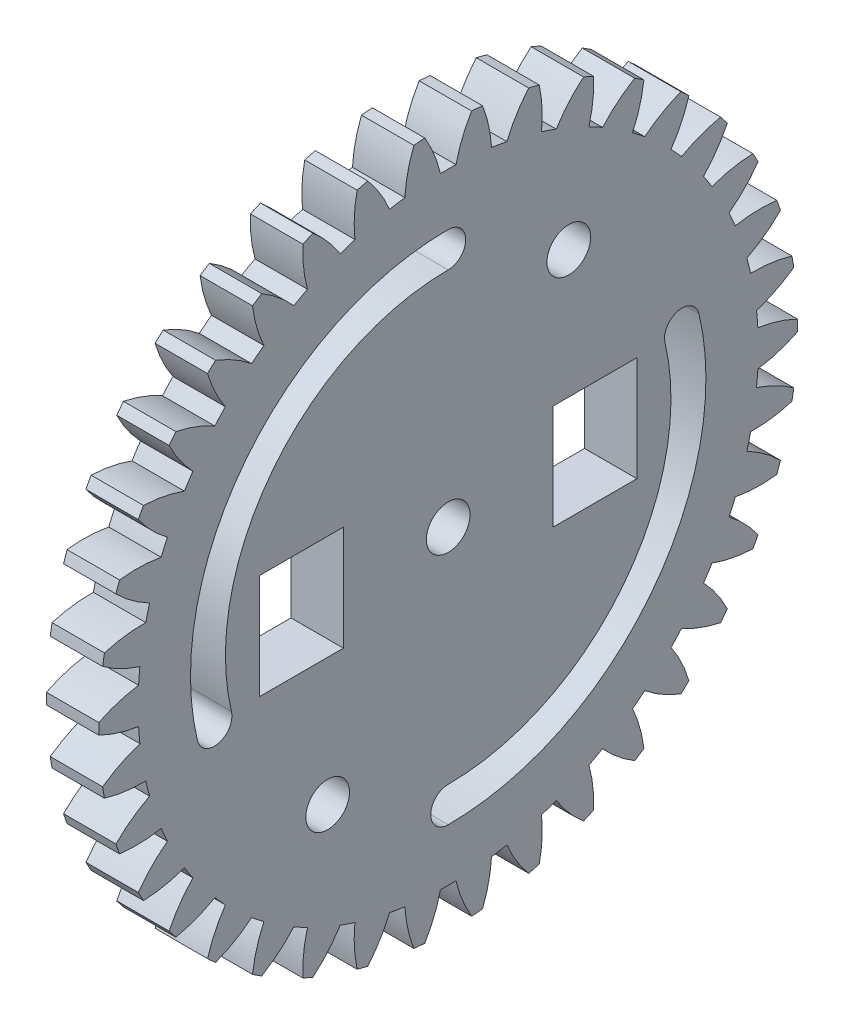
SolidWorks part; units mm, degrees
ref_plane "Plane1" through (0, 0, 0) normal (0, 0, 1) x (1, 0, 0)
ref_plane "Plane2" through (0, 0, 0) normal (0, 1, 0) x (1, 0, 0)
ref_plane "Plane3" through (0, 0, 0) normal (1, 0, 0) x (0, 0, -1)
sketch "HoldingSke" plane through (0, 0, 0) normal (0, 1, 0) x (1, 0, 0)
  line L0 (0, 0) -> (0.394, -0.3078)
  line L1 (-15, 0) -> (100, 0) construction
  line L2 (0, 0) -> (-2.1039, 2.3779)
  line L3 (0, 0) -> (-11.863, 4.5341)
  line L4 (0, 0) -> (6.8053, 5.3169)
  line L5 (0, 0) -> (-46.8476, -17.4728)
  line L6 (0, 0) -> (-4.9738, -3.3558)
  line L7 (-2.1039, 2.3779) -> (8.6586, 51.2059)
  line L8 (-76.2, 54.61) -> (-75.5, 54.61)
  line L9 (-71.009, 38.7566) -> (-53.1078, 45.2721)
  line L10 (-76.2, 71.12) -> (104.1128, 71.12)
  line L11 (0, 0) -> (-6, 0)
  line L12 (-76.2, 101.6) -> (-76.133, 101.6)
  line L13 (24.9733, 27.94) -> (52.9518, 28.4284)
  line L14 (24.9733, 27.94) -> (24.9743, 27.94)
  line L15 (24.9733, 27.94) -> (100.4006, 29.5858)
  line L16 (-63.627, -2) -> (-12.827, -2)
  circle A0 centre (0, 0) radius 2
  circle A1 centre (0, 0) radius 35.499
  circle A2 centre (0, 0) radius 37.5
  circle A3 centre (0, 0) radius 2
  dimension "MHD" = 70.998
  dimension "Hub_dia" = 75
  dimension "Bore" = 4
  dimension "MBD" = 4
  dimension "Num_teeth" = 38
  dimension "Pitch" = 0.5
  dimension "Overall_len" = 50
  dimension "Show_teeth" = 38
  dimension "Thickness" = 6
  dimension "OAL" = 50.0001
  dimension "T_dim" = 0.7
  dimension "Ap" = 20
  dimension "H" = 19.05
  dimension "Pitch_radius" = 180.3128
  dimension "Width" = 6
  dimension "Backlash" = 0.067
  dimension "Addendum_fac" = 1
  dimension "Dedendum_fac" = 1.25
  dimension "Clearance_fac" = 0.25
  dimension "Dedendum_add" = 0.001
  dimension "Module" = 2
sketch "BasProSke" plane through (0, 0, 0) normal (0, 1, 0) x (1, 0, 0)
  line L0 (-10, 0) -> (60, 0) construction
  line L1 (0, 0) -> (0, 40)
  line L2 (0, 0) -> (6, 0)
  line L3 (6, 0) -> (6, 40)
  line L4 (6, 40) -> (0, 40)
  dimension "Thickness" = 6
  dimension "Diameter" = 80
revolve "Base-Revolve" add sketch "BasProSke" angle 360 about L0
sketch "TooCutSke" plane through (0, 0, 0) normal (1, 0, 0) x (0, 0, -1)
  line L1 (0, 0) -> (0, 107) construction
  line L2 (0, 0) -> (-1.6876, 37.9625) construction
  line L3 (0, 0) -> (-6.2714, 75.685) construction
  line L4 (-1.6876, 37.9625) -> (-3.1357, 37.8425) construction
  arc A0 (0.8886, 35.4879) -> (-0.8886, 35.4879) centre (0, 0) ccw
  arc A1 (2.6915, 39.9348) -> (-2.6915, 39.9348) centre (0, 0) ccw
  circle A2 centre (0, 0) radius 38 construction
  circle A3 centre (0, 0) radius 35.7083 construction
  arc A4 (-0.8886, 35.4879) -> (-2.6915, 39.9348) centre (-15.6997, 32.0718) ccw
  arc A5 (2.6915, 39.9348) -> (0.8886, 35.4879) centre (15.6997, 32.0718) ccw
  dimension "Root_dia" = 70.998
  dimension "Overcut_dia" = 80.0508
  dimension "Pitch_dia" = 76
  dimension "Base_dia" = 71.4166
  dimension "Flank_rad" = 15.2
  dimension "Half_ang" = 4.737
  dimension "Half_CT" = 1.4531
extrude "ToothCut" cut sketch "TooCutSke" along normal through all
fillet "Breaks" [suppressed] radius 0.04
fillet "RootFillets" [suppressed] radius 0.501
pattern_circular "TeethCuts" count 38 every 9.474 about axis through (-10, 0, 0) along (1, 0, 0) of "ToothCut", "RootFillets", "Breaks"
sketch "HubNeaOneSke" plane through (0, 0, 0) normal (-1, 0, 0) x (0, 0, 1)
  circle A0 centre (0, 0) radius 35.499
  dimension "Diameter" = 70.998
extrude "HubNearOne" [suppressed] add sketch "HubNeaOneSke" along normal blind 44.0001
sketch "HubNeaBotSke" plane through (0, 0, 0) normal (-1, 0, 0) x (0, 0, 1)
  circle A0 centre (0, 0) radius 35.499
  dimension "Diameter" = 70.998
extrude "HubNearBoth" [suppressed] add sketch "HubNeaBotSke" along normal blind 22
ref_plane "FarPln" through (6, 0, 0) normal (1, 0, 0) x (0, 0, -1)
sketch "HubFarSke" plane through (6, 0, 0) normal (1, 0, 0) x (0, 0, -1)
  circle A0 centre (0, 0) radius 35.499
  dimension "Diameter" = 70.998
extrude "HubFar" [suppressed] add sketch "HubFarSke" along normal blind 22
sketch "BorSke" plane through (0, 0, 0) normal (1, 0, 0) x (0, 0, -1)
  circle A0 centre (0, 0) radius 2.5
  dimension "Diameter" = 5
extrude "Bore" cut sketch "BorSke" along normal mid plane 100.0001
sketch "KeySke" plane through (0, 0, 0) normal (1, 0, 0) x (0, 0, -1)
  line L0 (-0.8, 0) -> (-0.8, 2.7)
  line L1 (-0.8, 2.7) -> (0.8, 2.7)
  line L2 (0.8, 2.7) -> (0.8, 0)
  line L3 (0, 0) -> (0, 34) construction
  line L4 (-0.8, 0) -> (0.8, 0)
  dimension "Offset" = 2.7
  dimension "Width" = 1.6
extrude "Keyway" [suppressed] cut sketch "KeySke" along normal mid plane 100.0001
pattern_circular "Keyway2" [suppressed] count 2 every 90 about axis through (-10, 0, 0) along (1, 0, 0)
ref_plane "Plane4" through (16, 0, 0) normal (1, 0, 0) x (0, 0, -1)
sketch "Sketch1" plane through (16, 0, 0) normal (1, 0, 0) x (0, 0, -1)
  line L0 (-16.8, 0) -> (16.8, 0) construction
  line L1 (0, 0) -> (0, 31.4173) construction
  line L2 (-21.6, 6) -> (-12, 6)
  line L3 (-21.6, 6) -> (-21.6, -6)
  line L4 (-21.6, -6) -> (-12, -6)
  line L5 (-12, 6) -> (-12, -6)
  line L6 (-21.6, 6) -> (-12, -6) construction
  line L7 (-21.6, -6) -> (-12, 6) construction
  line L8 (12, 6) -> (21.6, 6)
  line L9 (12, 6) -> (12, -6)
  line L10 (12, -6) -> (21.6, -6)
  line L11 (21.6, 6) -> (21.6, -6)
  line L12 (12, 6) -> (21.6, -6) construction
  line L13 (12, -6) -> (21.6, 6) construction
  circle A0 centre (0, 0) radius 2.5 construction
  circle A1 centre (0, 0) radius 2.5
  arc A2 (-26.7608, -6.3331) -> (0, 27.5) centre (0, 0) cw construction
  arc A3 (0, 29.5) -> (-28.7071, -6.7937) centre (0, 0) ccw
  arc A4 (0, 25.5) -> (-24.8146, -5.8725) centre (0, 0) ccw
  arc A5 (0, 25.5) -> (0, 29.5) centre (0, 27.5) ccw
  arc A6 (-28.7071, -6.7937) -> (-24.8146, -5.8725) centre (-26.7608, -6.3331) ccw
  arc A7 (26.7608, 6.3331) -> (0, -27.5) centre (0, 0) cw construction
  arc A8 (0, -29.5) -> (28.7071, 6.7937) centre (0, 0) ccw
  arc A9 (0, -25.5) -> (24.8146, 5.8725) centre (0, 0) ccw
  arc A10 (0, -25.5) -> (0, -29.5) centre (0, -27.5) ccw
  arc A11 (28.7071, 6.7937) -> (24.8146, 5.8725) centre (26.7608, 6.3331) ccw
  circle A12 centre (0, 0) radius 27.5 construction
  circle A13 centre (-13.8, -20.6) radius 2.5
  circle A14 centre (13.8, 20.6) radius 2.5
  point P16 (-21.5686, 17.06)
  point P21 (21.5686, -17.06)
  dimension "D7" = 14.6
  dimension "D8" = 2
  dimension "D12" = 14.6
  dimension "D11" = 55
  dimension "D5" = 2
  dimension "D13" = 5
  dimension "D14" = 5
  dimension "D2" = 12
  dimension "D3" = 9.6
  dimension "D4" = 12
  dimension "D6" = 12
  dimension "D9" = 40
  dimension "D10" = 40
  dimension "D15" = 7.8
  dimension "D16" = 7.8
extrude "Cut-Extrude1" cut sketch "Sketch1" against normal blind 60
equation "' \"Module@HoldingSke\" = 6.35"
equation "' \"Num_teeth@HoldingSke\" = 12"
equation "' \"Ap@HoldingSke\" =  20"
equation "' \"Ap@HoldingSke\" = 20"
equation "' \"Width@HoldingSke\" = 0.5 * 25.4"
equation "' \"Hub_dia@HoldingSke\"= 1 * 25.4"
equation "' \"Hub_dia@HoldingSke\" = 1 * 25.4"
equation "' \"Overall_len@HoldingSke\" = 1.0 * 25.4"
equation "' \"Bore@HoldingSke\" = 0.75 * 25.4"
equation "' \"T_dim@HoldingSke\" = 0.1 * 25.4"
equation "' \"Width@KeySke\" = 0.25 * 25.4"
equation "' \"Show_teeth@HoldingSke\" = 13"
equation "' \"Backlash@HoldingSke\" = 0.009 * 25.4"
equation "' \"Addendum_fac@HoldingSke\" = 1.0"
equation "' \"Dedendum_fac@HoldingSke\" = 1.25"
equation "' \"Dedendum_add@HoldingSke\" = 0.00005 * 25.4"
equation "' \"Clearance_fac@HoldingSke\" = 0.25"
equation "\"Pitch@HoldingSke\" = 1 / \"Module@HoldingSke\""
equation "\"Overcut_dia@TooCutSke\" = (\"Num_teeth@HoldingSke\" + 2 * \"Addendum_fac@HoldingSke\") / \"Pitch@HoldingSke\" + 0.002 * 25.4"
equation "\"Pitch_dia@TooCutSke\" = \"Num_teeth@HoldingSke\" / \"Pitch@HoldingSke\""
equation "\"Base_dia@TooCutSke\" = \"Num_teeth@HoldingSke\" / \"Pitch@HoldingSke\" * cos((\"Ap@HoldingSke\"  * 3.14159265 / 180))"
equation "\"Root_dia@TooCutSke\" = (\"Num_teeth@HoldingSke\" + 2) / \"Pitch@HoldingSke\" - 2 * (\"Addendum_fac@HoldingSke\" + \"Dedendum_fac@HoldingSke\") / \"Pitch@HoldingSke\" - \"Dedendum_add@HoldingSke\" * 2"
equation "\"Half_ang@TooCutSke\" = 180 / \"Num_teeth@HoldingSke\""
equation "\"Half_CT@TooCutSke\" = \"Num_teeth@HoldingSke\" / \"Pitch@HoldingSke\" * sin((3.14159265 / 2 / \"Num_teeth@HoldingSke\")) / 2 - 7 * \"Backlash@HoldingSke\" / 4"
equation "\"Flank_rad@TooCutSke\" = \"Num_teeth@HoldingSke\" / \"Pitch@HoldingSke\" / 5"
equation "\"Radius@RootFillets\" = \"Clearance_fac@HoldingSke\" / \"Pitch@HoldingSke\" + \"Dedendum_add@HoldingSke\""
equation "\"Break_rad@Breaks\" = 0.02 / \"Pitch@HoldingSke\""
equation "\"Thickness@HoldingSke\" = \"Width@HoldingSke\""
equation "\"OAL@HoldingSke\" = \"Thickness@HoldingSke\""
equation "\"MHD@HoldingSke\" = (\"Num_teeth@HoldingSke\" + 2) / \"Pitch@HoldingSke\" - 2 * (\"Addendum_fac@HoldingSke\" + \"Dedendum_fac@HoldingSke\")  / \"Pitch@HoldingSke\" - \"Dedendum_add@HoldingSke\" * 2"
equation "\"MBD@HoldingSke\" = (\"Num_teeth@HoldingSke\" + 2) / \"Pitch@HoldingSke\" - 2 * (\"Addendum_fac@HoldingSke\" + \"Dedendum_fac@HoldingSke\")  / \"Pitch@HoldingSke\" - \"Dedendum_add@HoldingSke\" * 2 - 0.002 * 25.4"
equation "\"MHD@HoldingSke\" = ((sgn( \"MHD@HoldingSke\" - \"Hub_dia@HoldingSke\" )-1)*( \"MHD@HoldingSke\" - \"Hub_dia@HoldingSke\" ))/-2+ \"Hub_dia@HoldingSke\""
equation "\"MBD@HoldingSke\" = ((sgn( \"MBD@HoldingSke\" - \"Bore@HoldingSke\" )-1)*( \"MBD@HoldingSke\" - \"Bore@HoldingSke\" ))/-2+ \"Bore@HoldingSke\""
equation "\"OAL@HoldingSke\" = ((sgn( \"OAL@HoldingSke\" - \"Overall_len@HoldingSke\" )+1)*( \"OAL@HoldingSke\" - \"Overall_len@HoldingSke\" ))/2 + \"Overall_len@HoldingSke\" + 0.000002 * 25.4"
equation "\"Num_teeth@TeethCuts\" = int( \"Show_teeth@HoldingSke\" ) + 1"
equation "\"Num_teeth@TeethCuts\" = ((sgn( \"Num_teeth@TeethCuts\" - \"Num_teeth@HoldingSke\" )-1)*( \"Num_teeth@TeethCuts\" - \"Num_teeth@HoldingSke\" ))/-2+ \"Num_teeth@HoldingSke\""
equation "\"Num_teeth@TeethCuts\" = ((sgn( \"Num_teeth@TeethCuts\" - 2.0)+1)*( \"Num_teeth@TeethCuts\" - 2.0))/2 +2.0"
equation "\"Angle@TeethCuts\" = 360.0 / \"Num_teeth@HoldingSke\""
equation "\"Diameter@BasProSke\" = (\"Num_teeth@HoldingSke\" + 2 * \"Addendum_fac@HoldingSke\") / \"Pitch@HoldingSke\""
equation "\"Thickness@BasProSke\"  = \"Thickness@HoldingSke\""
equation "' \"Fillet_rad@BasProSke\" =  \"Thickness@HoldingSke\" * 0.05"
equation "' \"Fillet_rad@BasProSke\" = \"Thickness@HoldingSke\" * 0.05"
equation "\"MHD@HoldingSke\" = ((sgn( \"MHD@HoldingSke\" - \"Root_dia@TooCutSke\" )-1)*( \"MHD@HoldingSke\" - \"Root_dia@TooCutSke\" ))/-2+ \"Root_dia@TooCutSke\""
equation "\"Diameter@HubNeaOneSke\" = \"MHD@HoldingSke\""
equation "\"Length@HubNearOne\" = \"OAL@HoldingSke\" - \"Thickness@BasProSke\""
equation "\"Diameter@HubNeaBotSke\" = \"MHD@HoldingSke\""
equation "\"Length@HubNearBoth\" = ( \"OAL@HoldingSke\" - \"Thickness@BasProSke\" ) / 2.0"
equation "\"Thickness@FarPln\" = \"Thickness@BasProSke\""
equation "\"Diameter@HubFarSke\" = \"MHD@HoldingSke\""
equation "\"Length@HubFar\" = ( \"OAL@HoldingSke\" - \"Thickness@BasProSke\" ) / 2.0"
equation "\"D1@Bore\" = \"OAL@HoldingSke\" * 2.0"
equation "\"D1@Keyway\" = \"OAL@HoldingSke\" * 2.0"
equation "\"Offset@KeySke\" = \"T_dim@HoldingSke\" + \"MBD@HoldingSke\" / 2.0"
